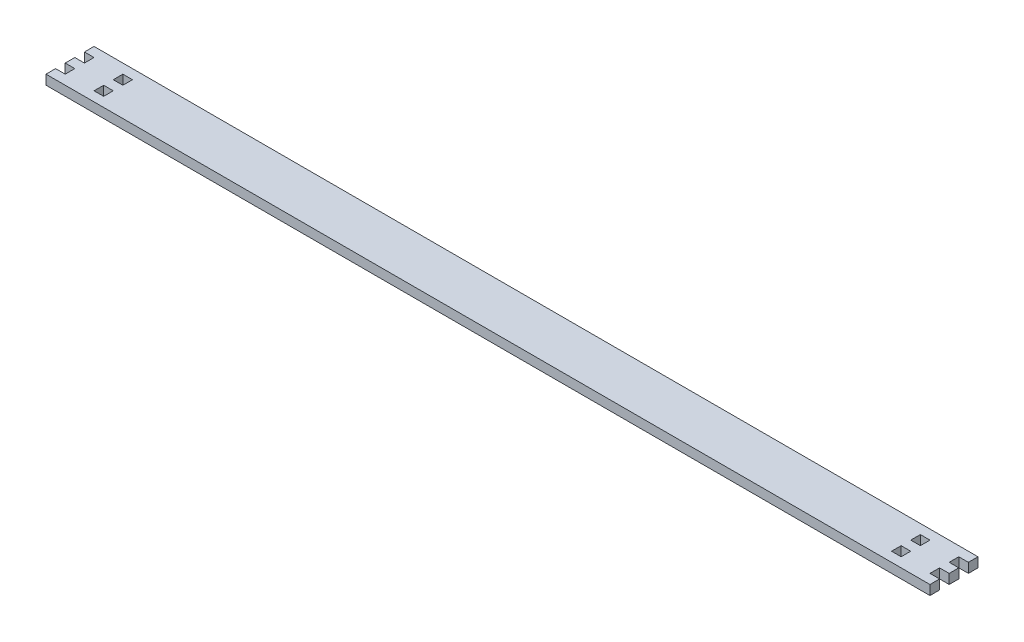
SolidWorks part; units mm, degrees
ref_plane "Спереди" through (0, 0, 0) normal (0, 0, 1) x (1, 0, 0)
ref_plane "Сверху" through (0, 0, 0) normal (0, 1, 0) x (1, 0, 0)
ref_plane "Справа" through (0, 0, 0) normal (1, 0, 0) x (0, 0, -1)
sketch "Эскиз1" plane through (0, 0, 0) normal (0, 1, 0) x (1, 0, 0)
  line L0 (-450, 5) -> (-450, 15)
  line L1 (450, -25) -> (-450, -25)
  line L3 (450, 25) -> (-450, 25)
  line L4 (-450, -15) -> (-450, -5)
  line L5 (450, -25) -> (-450, 25) construction
  line L7 (-450, -5) -> (-460, -5)
  line L8 (-450, 15) -> (-460, 15)
  line L9 (-450, 5) -> (-460, 5)
  line L10 (-460, -5) -> (-460, 5)
  line L11 (-450, 25) -> (-460, 25)
  line L12 (-460, 15) -> (-460, 25)
  line L13 (-450, -25) -> (-460, -25)
  line L14 (-450, -15) -> (-460, -15)
  line L15 (-460, -25) -> (-460, -15)
  line L16 (-420, -15) -> (-420, -5)
  line L17 (-410, -15) -> (-420, -15)
  line L18 (-410, -15) -> (-410, -5)
  line L19 (-410, -5) -> (-420, -5)
  line L20 (-420, 15) -> (-420, 5)
  line L21 (-410, 5) -> (-420, 5)
  line L22 (-410, 5) -> (-410, 15)
  line L23 (-410, 15) -> (-420, 15)
  line L24 (0, 0) -> (0, -47.9372) construction
  line L25 (-420, -25) -> (-420, -23.3333) [skipped]
  line L26 (410, 15) -> (420, 15)
  line L27 (-420, -5) -> (-420, 5) [skipped]
  line L28 (-420, 23.3333) -> (-420, 25) [skipped]
  line L29 (410, 5) -> (410, 15)
  line L30 (410, 5) -> (420, 5)
  line L31 (420, 15) -> (420, 5)
  line L32 (410, -5) -> (420, -5)
  line L33 (410, -15) -> (410, -5)
  line L34 (410, -15) -> (420, -15)
  line L35 (420, -15) -> (420, -5)
  line L36 (460, -25) -> (460, -15)
  line L37 (450, -15) -> (460, -15)
  line L39 (460, 15) -> (460, 25)
  line L41 (460, -5) -> (460, 5)
  line L42 (450, 5) -> (460, 5)
  line L43 (450, 15) -> (460, 15)
  line L44 (450, -5) -> (460, -5)
  line L45 (450, -15) -> (450, -5)
  line L46 (450, 5) -> (450, 15)
  line L47 (460, 25) -> (450, 25)
  line L48 (460, -25) -> (450, -25)
  point P0 (0, 0)
  point P6 (-347.4847, 25)
  point P9 (-460, 0)
  dimension "D1" = 900
  dimension "D2" = 50
  dimension "D3" = 2
  dimension "D4" = 2
  dimension "D5" = 112.5153
  dimension "D6" = 2
extrude "Бобышка-Вытянуть1" add sketch "Эскиз1" along normal blind 10
